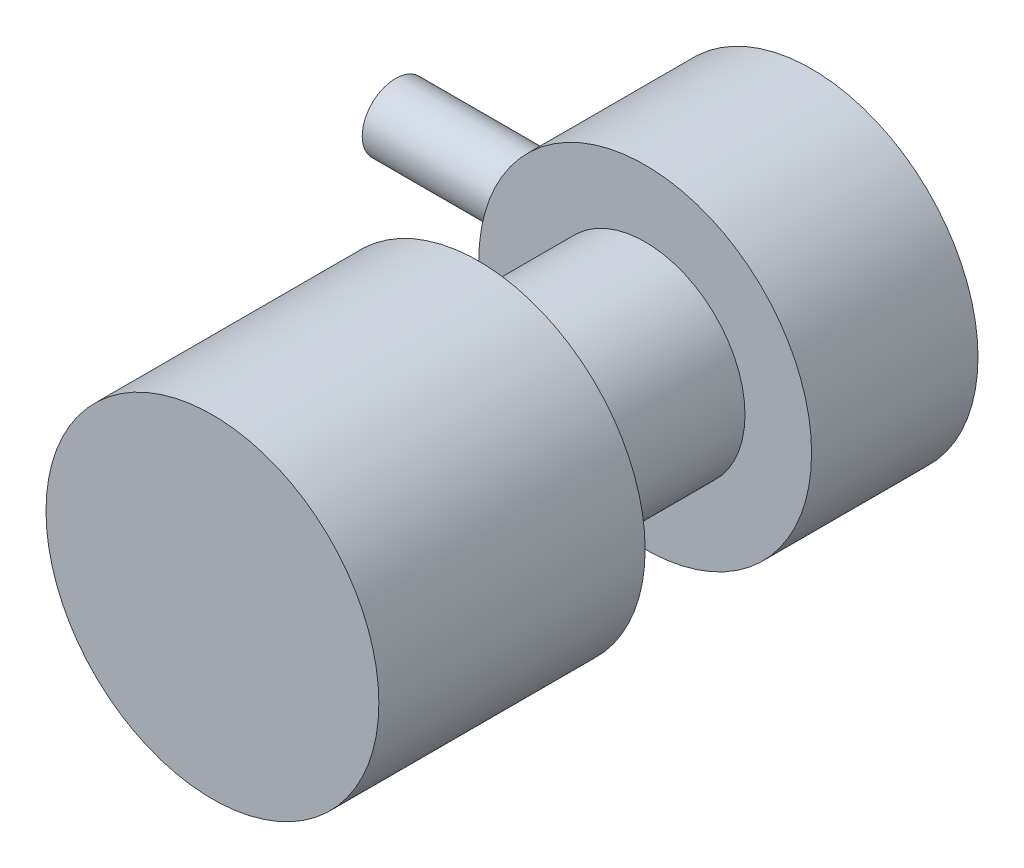
SolidWorks part; units mm, degrees
ref_plane "Front Plane" through (0, 0, 0) normal (0, 0, 1) x (1, 0, 0)
ref_plane "Top Plane" through (0, 0, 0) normal (0, 1, 0) x (1, 0, 0)
ref_plane "Right Plane" through (0, 0, 0) normal (1, 0, 0) x (0, 0, -1)
sketch "Sketch2" plane through (0, 0, 0) normal (0, 0, 1) x (1, 0, 0)
  line L0 (0, 0) -> (0, 17.5092) construction
  line L1 (0, 0) -> (9.7726, 0) construction
  circle A0 centre (0, 0) radius 5
extrude "Boss-Extrude1" add sketch "Sketch2" along normal blind 5
sketch "Sketch3" plane through (0, 0, 5) normal (0, 0, 1) x (1, 0, 0)
  circle A0 centre (0, 0) radius 3
extrude "Boss-Extrude2" add sketch "Sketch3" along normal blind 5
sketch "Sketch4" plane through (0, 0, 10) normal (0, 0, 1) x (1, 0, 0)
  circle A0 centre (0, 0) radius 5
extrude "Boss-Extrude3" add sketch "Sketch4" along normal blind 8
ref_plane "Plane1" through (0, 0, 0) normal (-1, 0, 0) x (0, 0, 1)
sketch "Sketch5" plane through (0, 0, 0) normal (-1, 0, 0) x (0, 0, 1)
  circle A0 centre (2.5, 0) radius 1
  dimension "D1" = 2.5
  dimension "D2" = 2
extrude "Boss-Extrude4" add sketch "Sketch5" along normal blind 10
